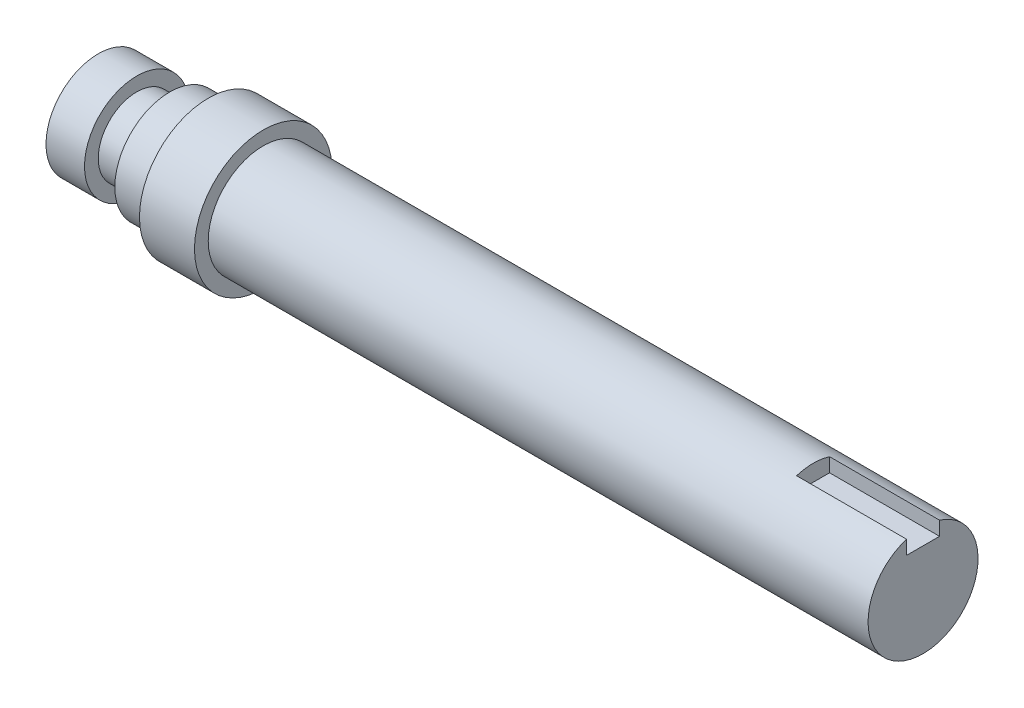
SolidWorks part; units mm, degrees
material "1023 Carbon Steel Sheet (SS)"
ref_plane "Front Plane" through (0, 0, 0) normal (0, 0, 1) x (1, 0, 0)
ref_plane "Top Plane" through (0, 0, 0) normal (0, 1, 0) x (1, 0, 0)
ref_plane "Right Plane" through (0, 0, 0) normal (1, 0, 0) x (0, 0, -1)
sketch "Sketch1" plane through (0, 0, 0) normal (0, 0, 1) x (1, 0, 0)
  line L0 (0, 0) -> (0, 10)
  line L1 (0, 10) -> (-120, 10)
  line L2 (-120, 10) -> (-120, 12.5)
  line L3 (-120, 12.5) -> (-130, 12.5)
  line L4 (-130, 12.5) -> (-130, 9.9796)
  line L5 (-130, 9.9796) -> (-137, 9.9796)
  line L6 (-137, 9.9796) -> (-137, 7)
  line L7 (-137, 7) -> (-143, 7)
  line L8 (-143, 7) -> (-143, 9.5)
  line L9 (-143, 9.5) -> (-150, 9.5)
  line L10 (-150, 9.5) -> (-150, 0)
  line L11 (-150, 0) -> (0, 0)
  point P3 (-140, 7)
  dimension "D1" = 3
  dimension "D2" = 10
  dimension "D3" = 7
  dimension "D4" = 7
  dimension "D5" = 9.5
  dimension "D6" = 10
  dimension "D7" = 3
  dimension "D8" = 12.5
  dimension "D9" = 150
revolve "Revolve1" add sketch "Sketch1" angle 360 about L11
sketch "Sketch2" plane through (0, 0, 0) normal (0, 0, 1) x (1, 0, 0)
  line L0 (0, 10) -> (-120, 10) construction
  line L2 (0, 12) -> (0, 7)
  line L3 (0, 7) -> (-20, 7)
  line L4 (-20, 12) -> (-20, 7)
  line L5 (-3.3333, 12) -> (-20, 7) construction
  line L6 (0, 7) -> (-16.6667, 12) construction
  line L8 (-20, 12) -> (0, 12)
  point P0 (-10, 10)
  dimension "D2" = 3
  dimension "D3" = 2
extrude "Cut-Extrude1" cut sketch "Sketch2" against normal mid plane 6
